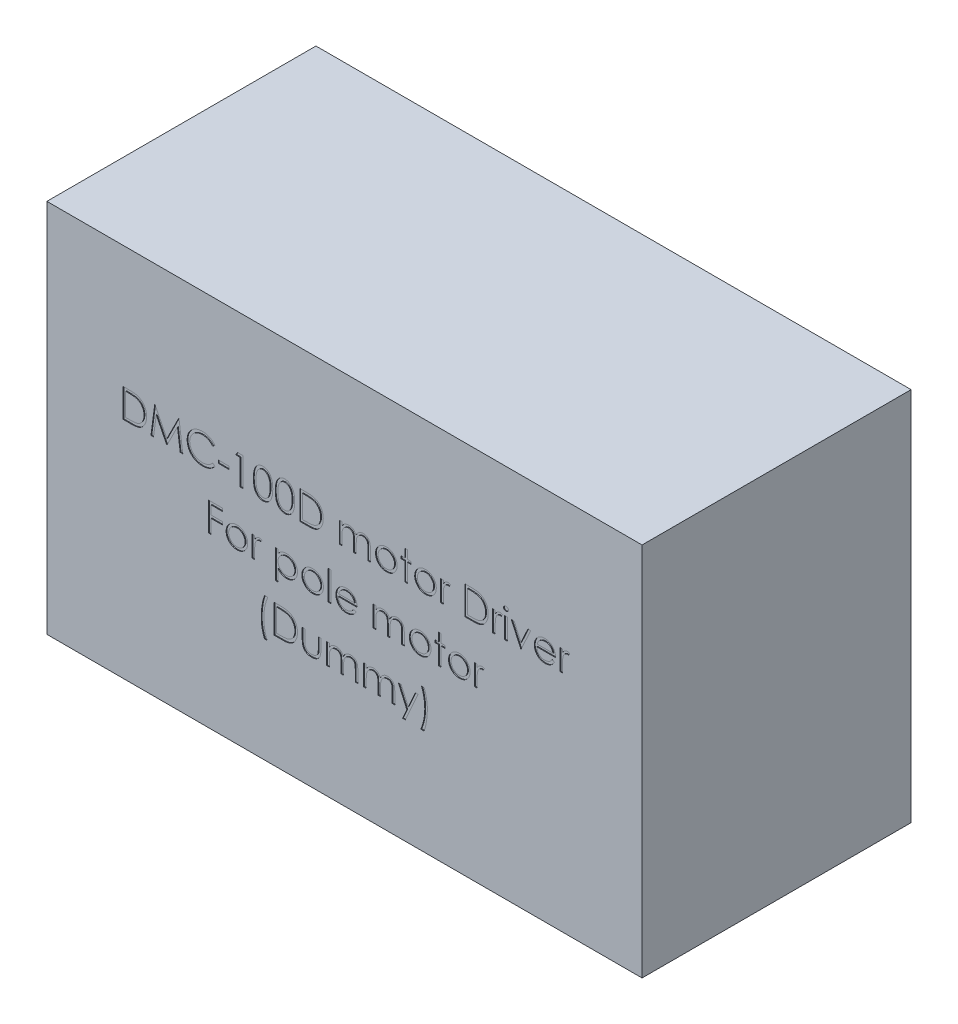
SolidWorks part; units mm, degrees
ref_plane "정면" through (0, 0, 0) normal (0, 0, 1) x (1, 0, 0)
ref_plane "윗면" through (0, 0, 0) normal (0, 1, 0) x (1, 0, 0)
ref_plane "우측면" through (0, 0, 0) normal (1, 0, 0) x (0, 0, -1)
sketch "스케치1" plane through (0, 0, 0) normal (0, 0, 1) x (1, 0, 0)
  line L1 (-36.5, 23) -> (36.5, 23)
  line L2 (-36.5, 23) -> (-36.5, -23)
  line L3 (-36.5, -23) -> (36.5, -23)
  line L4 (36.5, 23) -> (36.5, -23)
  line L5 (-36.5, 23) -> (36.5, -23) construction
  line L6 (-36.5, -23) -> (36.5, 23) construction
  point P0 (0, 0)
  dimension "D1" = 73
  dimension "D2" = 46
extrude "보스-돌출1" add sketch "스케치1" along normal blind 33
sketch "스케치2" plane through (0, 0, 33) normal (0, 0, 1) x (1, 0, 0)
  line L0 (-36.5, 4.5149) -> (36.5, 4.5149) construction
  line L1 (-36.5, 23) -> (-36.5, -23) construction
  line L2 (36.5, -23) -> (36.5, 23) construction
  text T0 "DMC-100D motor Driver\r\nFor pole motor\r\n(Dummy)\r\n"
extrude "컷-돌출1" cut sketch "스케치2" against normal blind 0.1
